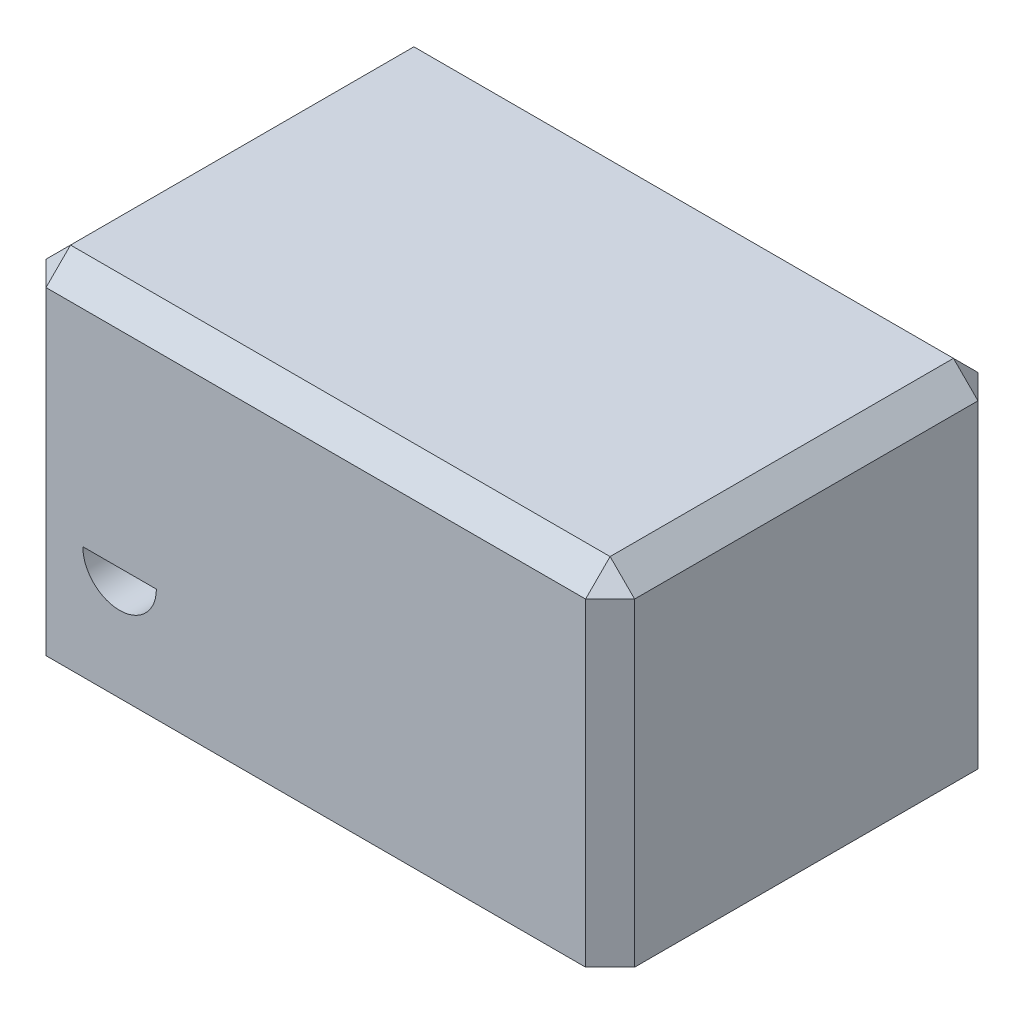
SolidWorks part; units mm, degrees
ref_plane "Front Plane" through (0, 0, 0) normal (0, 0, 1) x (1, 0, 0)
ref_plane "Top Plane" through (0, 0, 0) normal (0, 1, 0) x (1, 0, 0)
ref_plane "Right Plane" through (0, 0, 0) normal (1, 0, 0) x (0, 0, -1)
sketch "Sketch1" plane through (0, 0, 0) normal (0, 0, 1) x (1, 0, 0)
  line L1 (0, 0) -> (120, 0)
  line L2 (0, 0) -> (0, 70)
  line L3 (0, 70) -> (120, 70)
  line L4 (120, 0) -> (120, 70)
  dimension "D1" = 120
  dimension "D2" = 70
extrude "Boss-Extrude3" add sketch "Sketch1" against normal blind 80 contours L2 L3 L4 L1
chamfer "Chamfer2" distance 5 angle 45 8 edges at (120, 35, 0) (120, 35, -80) (120, 70, -40) (60, 70, -80) (60, 70, 0) (0, 35, -80) (0, 70, -40) (0, 35, 0)
sketch "Sketch5" plane through (0, 0, 0) normal (0, 0, 1) x (1, 0, 0)
  line L0 (5, 0) -> (115, 0) construction
  line L1 (5, 65) -> (5, 0) construction
  line L2 (12.5, 23) -> (27.5, 23)
  arc A0 (12.5, 23) -> (27.5, 23) centre (20, 23) ccw
  dimension "D1" = 15
  dimension "D2" = 23
  dimension "D3" = 15
extrude "Cut-Extrude1" cut sketch "Sketch5" against normal through all contours L2 A0
